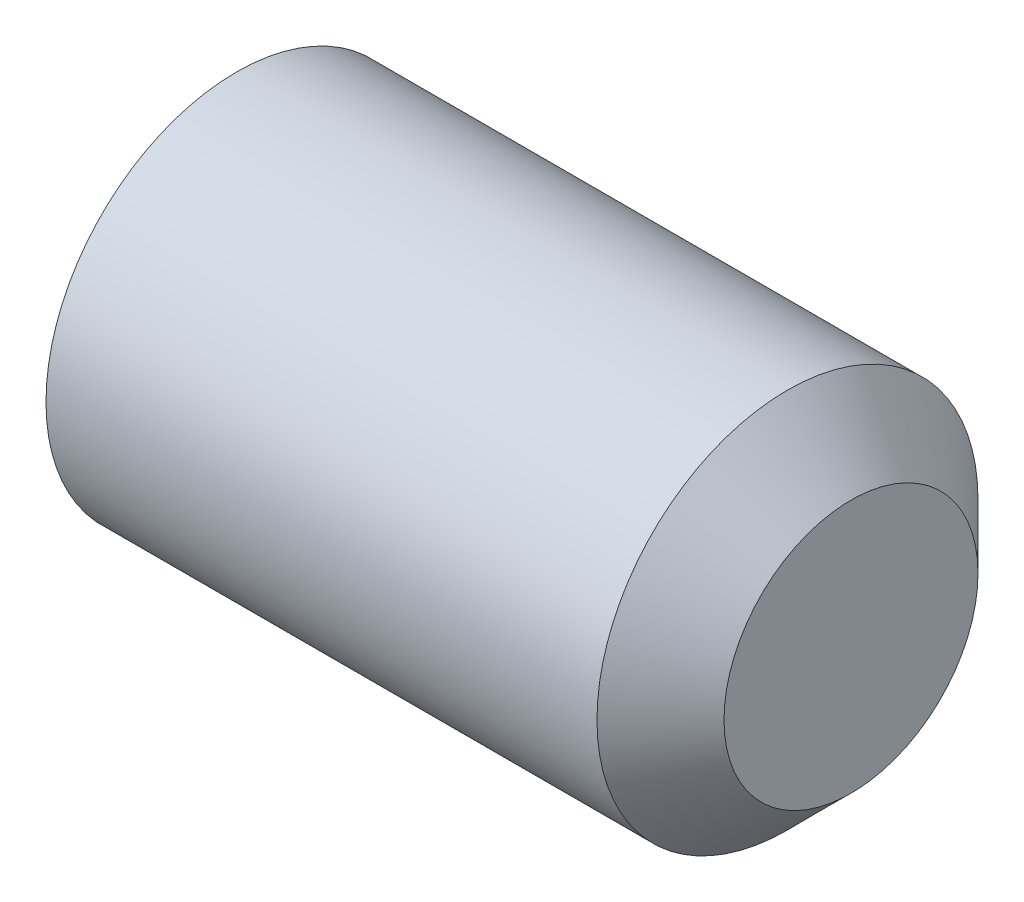
SolidWorks part; units mm, degrees
revolve "BaseBody" add sketch "BodySke" angle 360 about L5
sketch "BodySke" plane through (0, 0, 0) normal (0, 0, 1) x (1, 0, 0)
  line L0 (0, 0) -> (0, 1.2195)
  line L1 (0, 1.2195) -> (0.1619, 1.5)
  line L2 (0.1619, 1.5) -> (4.5, 1.5)
  line L3 (4.5, 1.5) -> (5, 1)
  line L4 (5, 0) -> (0, 0)
  line L5 (-12.7, 0) -> (88.9, 0) construction
  line L6 (5, 1) -> (5, 0)
  line L7 (5, 1) -> (5, 10.525) construction
  line L8 (0, -1.2195) -> (0.1619, -1.5) construction
  line L9 (0.5, 15.875) -> (0.5, -3.175) construction
  line L10 (4.5, -1.5) -> (5, -1) construction
  dimension "Diameter" = 3
  dimension "Drive_ch_ang" = 60
  dimension "Minor_dia" = 2.439
  dimension "Cup_nose_ang" = 45
  dimension "Cup_dia" = 2
  dimension "Length" = 5
  dimension "Advance" = 0.5
cosmetic thread "ThreadCosmetic" [suppressed] parameters "Thread_minor"=2.439
ref_plane "Plane1" through (0, 0, 0) normal (0, 0, 1) x (1, 0, 0)
ref_plane "Plane2" through (0, 0, 0) normal (0, 1, 0) x (1, 0, 0)
ref_plane "Plane3" through (0, 0, 0) normal (1, 0, 0) x (0, 0, -1)
other "Configuration Table"
sketch "Sketch2" plane through (0, 0, 0) normal (-1, 0, 0) x (0, 0, 1)
  line L0 (0.433, 0.75) -> (-0.433, 0.75)
  line L1 (-0.433, 0.75) -> (-0.866, 0)
  line L2 (0.433, 0.75) -> (0.866, 0)
  line L3 (0.433, -0.75) -> (0.866, 0)
  line L4 (0.433, -0.75) -> (-0.433, -0.75)
  line L5 (-0.433, -0.75) -> (-0.866, 0)
  dimension "Hex_size" = 1.5
  dimension "D2" = 0.75
  dimension "D3" = 0.75
extrude "Hex" cut sketch "Sketch2" against normal blind 2
sketch "ThdSchSke" plane through (0, 0, 0) normal (0, 0, 1) x (1, 0, 0)
  line L0 (0.1619, -1.2195) -> (-0.0345, -1.5)
  line L1 (0.1619, -1.2195) -> (0.3584, -1.5)
  line L2 (0.3584, -1.5) -> (0.3584, -1.875)
  line L3 (-3.175, 0) -> (5.1513, 0) construction
  line L5 (0.3584, -1.875) -> (-0.0345, -1.875)
  line L6 (-0.0345, -1.875) -> (-0.0345, -1.5)
  line L8 (0.1619, 1.5) -> (0.1619, -1.5) construction
  dimension "Thread_minor" = 2.439
  dimension "Diameter" = 3
revolve "ThreadSchematic" [suppressed] cut sketch "ThdSchSke" angle 360 about L3
pattern_linear "ThdSchPat" [suppressed]
equation "\"D2@Sketch2\" = \"Hex_size@Sketch2\" / 2"
equation "\"D3@Sketch2\" = \"Hex_size@Sketch2\" / 2"
equation "\"Thread_minor@ThreadCosmetic\" = \"Minor_dia@BodySke\""
equation "\"Thread_minor@ThdSchSke\" = \"Thread_minor@ThreadCosmetic\""
equation "\"Diameter@ThdSchSke\" = \"Diameter@BodySke\""
equation "\"Overcut@ThdSchSke\" = \"Diameter@BodySke\" * 1.25"
equation "\"Num_threads@ThdSchPat\" = int( (\"Length@BodySke\" - ( ( ( \"Diameter@BodySke\" - \"Minor_dia@BodySke\" ) * 0.5 ) / tan( \"Drive_ch_ang@BodySke\" * 0.017453292 ) ) - ( ( ( \"Diameter@BodySke\" - \"Cup_dia@BodySke\" ) * 0.5 ) * tan( \"Cup_nose_ang@BodySke\" * 0.017453292 ) ) ) / \"Advance@BodySke\" + 0.999 )  + 1"
equation "\"Advance@ThdSchPat\" = (\"Length@BodySke\" - ( ( ( \"Diameter@BodySke\" - \"Minor_dia@BodySke\" ) * 0.5 ) / tan( \"Drive_ch_ang@BodySke\" * 0.017453292 ) ) - ( ( ( \"Diameter@BodySke\" - \"Cup_dia@BodySke\" ) * 0.5 ) * tan( \"Cup_nose_ang@BodySke\" * 0.017453292 ) ) ) /  (\"Num_threads@ThdSchPat\" - 1) 'relax it"
equation "' \"Num_threads@ThdSchPat\" = \"Num_threads@ThdSchPat\" - sgn( \"Num_threads@ThdSchPat\" - 1) '---chamfered tips only---"
